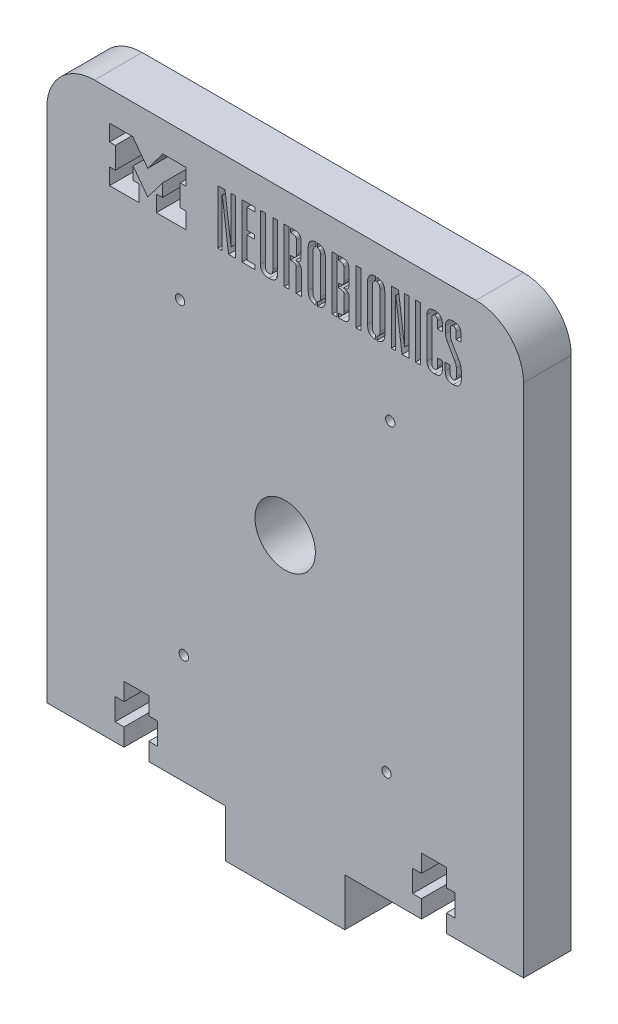
SolidWorks part; units mm, degrees
material "6061-T6 (SS)"
ref_plane "Front Plane" through (0, 0, 0) normal (0, 0, 1) x (1, 0, 0)
ref_plane "Top Plane" through (0, 0, 0) normal (0, 1, 0) x (1, 0, 0)
ref_plane "Right Plane" through (0, 0, 0) normal (1, 0, 0) x (0, 0, -1)
sketch "Sketch1" plane through (0, 0, 0) normal (0, 0, 1) x (1, 0, 0)
  line L1 (0, 0) -> (127, 0)
  line L2 (0, 0) -> (0, 150)
  line L3 (0, 150) -> (127, 150)
  line L4 (127, 0) -> (127, 150)
  dimension "D1" = 150
  dimension "D2" = 127
extrude "Boss-Extrude1" add sketch "Sketch1" along normal blind 12.7
sketch "Sketch2" plane through (0, 0, 12.7) normal (0, 0, 1) x (1, 0, 0)
  line L0 (63.5, 0) -> (63.5, 150) construction
  line L1 (0, 0) -> (127, 0) construction
  line L2 (127, 150) -> (0, 150) construction
  line L3 (23.876, 15.24) -> (23.876, 0) construction
  line L4 (20.574, 0) -> (27.178, 0)
  line L5 (20.574, 0) -> (20.574, 15.24)
  line L6 (20.574, 15.24) -> (27.178, 15.24)
  line L7 (27.178, 0) -> (27.178, 15.24)
  line L8 (18.2118, 10.541) -> (29.5402, 10.541)
  line L9 (18.2118, 10.541) -> (18.2118, 4.699)
  line L10 (18.2118, 4.699) -> (29.5402, 4.699)
  line L11 (29.5402, 10.541) -> (29.5402, 4.699)
  line L12 (18.2118, 7.62) -> (29.5402, 7.62) construction
  line L13 (108.7882, 7.62) -> (97.4598, 7.62) construction
  line L14 (103.124, 15.24) -> (103.124, 0) construction
  line L15 (97.4598, 10.541) -> (97.4598, 4.699)
  line L16 (108.7882, 4.699) -> (97.4598, 4.699)
  line L17 (108.7882, 10.541) -> (108.7882, 4.699)
  line L18 (108.7882, 10.541) -> (97.4598, 10.541)
  line L19 (99.822, 0) -> (99.822, 15.24)
  line L20 (106.426, 15.24) -> (99.822, 15.24)
  line L21 (106.426, 0) -> (106.426, 15.24)
  line L22 (106.426, 0) -> (99.822, 0)
  line L23 (0, 150) -> (0, 0) construction
  line M2 (0, 0) -> (127, 0)
  dimension "D1" = 6.604
  dimension "D2" = 11.3284
  dimension "D3" = 7.62
  dimension "D4" = 15.24
  dimension "D5" = 23.876
  dimension "D6" = 5.842
extrude "Cut-Extrude1" cut sketch "Sketch2" against normal through all contours L5 L8 L7 L6 | L5 L10 L7 L8 | L11 L8 L7 L10 | L9 L10 L5 L8 | L10 L5 L7 M2 | L21 L16 L19 M2 | L16 L21 L18 L19 | L21 L16 L17 L18 | L18 L21 L20 L19 | L16 L19 L18 L15
hole_wizard "1/4 Clearance Hole1" [suppressed] positions "Sketch5" profile "Sketch4" hole size "1/4" standard "ANSI Inch"
sketch "Sketch5" plane through (0, 0, 12.7) normal (0, 0, 1) x (1, 0, 0)
  line L4 (63.5, 150) -> (63.5, 0)
  line L5 (127, 150) -> (0, 150) construction
  line L6 (92.202, 0) -> (127, 0) construction
  point P9 (103.5, 25.4)
  point P13 (103.5, 76.2)
  dimension "D1" = 40
  dimension "D2" = 40
  dimension "D3" = 50.8
  dimension "D4" = 25.4
sketch "Sketch4" plane through (103.5, 25.4, 12.7) normal (1, 0, 0) x (0, -1, 0)
  line L0 (0, 0) -> (0, 27.4298)
  line L1 (0, 27.4298) -> (3.3782, 25.4)
  line L2 (3.3782, 25.4) -> (3.3782, 0)
  line L5 (3.3782, 0) -> (0, 0)
  line L10 (0, 27.4298) -> (-3.3782, 25.4) construction
  line L11 (0, -6.35) -> (0, 107.95) construction
  dimension "Hole Dia." = 6.7564
  dimension "Hole Depth" = 25.4
  dimension "Drill Angle" = 118
hole_wizard "CSK for 1/4 Flat Head Machine Screw2" [suppressed] positions "Sketch9" profile "Sketch8" countersink size "1/4" standard "Ansi Inch"
sketch "Sketch9" plane through (0, 0, 0) normal (0, 0, -1) x (-1, 0, 0)
  line L0 (-139.7, 174.498) -> (-127, 181.102) construction
  line L1 (-127, 155.702) -> (-139.7, 149.098) construction
  line L2 (-12.7, 149.098) -> (-25.4, 155.702) construction
  line L3 (-25.4, 181.102) -> (-12.7, 174.498) construction
  line L4 (-111.252, 114.3) -> (-104.648, 127) construction
  line L5 (-41.148, 127) -> (-47.752, 114.3) construction
  point P1 (-133.35, 177.8)
  point P5 (-133.35, 152.4)
  point P9 (-19.05, 152.4)
  point P13 (-19.05, 177.8)
  point P19 (-107.95, 120.65)
  point P23 (-44.45, 120.65)
sketch "Sketch8" plane through (133.35, 177.8, 0) normal (1, 0, 0) x (0, 1, 0)
  line L0 (0, 0) -> (0, 12.7)
  line L1 (0, 12.7) -> (3.2639, 12.7)
  line L2 (3.2639, 12.7) -> (3.2639, 3.6524)
  line L3 (3.2639, 3.6524) -> (6.4389, 0)
  line L5 (6.4389, 0) -> (0, 0)
  line L6 (-3.2639, 3.6524) -> (-6.4389, 0) construction
  line L11 (0, -6.35) -> (0, 107.95) construction
  dimension "Thru Hole Dia." = 6.5278
  dimension "Thru Hole Depth" = 12.7
  dimension "Near C'Sink Dia." = 12.8778
  dimension "Near C'Sink Angle" = 82
fillet "Fillet1" radius 12.7 2 edges at (127, 150, 6.35) (0, 150, 6.35)
sketch "Sketch11" plane through (0, 0, 0) normal (0, -1, 0) x (1, 0, 0)
  line L0 (27.178, 12.7) -> (99.822, 12.7) construction
  line L1 (47.625, 12.7) -> (79.375, 12.7)
  line L2 (47.625, 12.7) -> (47.625, 0)
  line L3 (47.625, 0) -> (79.375, 0)
  line L4 (79.375, 12.7) -> (79.375, 0)
  line L5 (27.178, 0) -> (99.822, 0) construction
  line L6 (63.5, 12.7) -> (63.5, 0) construction
  line L7 (27.178, 0) -> (27.178, 12.7) construction
  line L8 (99.822, 0) -> (99.822, 12.7) construction
  dimension "D1" = 31.75
extrude "Boss-Extrude2" add sketch "Sketch11" along normal blind 12.7
ref_plane "Plane1" through (63.5, 0, 0) normal (1, 0, 0) x (0, 0, -1)
mirror "Mirror2" [suppressed] about plane through (63.5, 0, 0) normal (1, 0, 0)
sketch "Sketch19" plane through (0, 0, 12.7) normal (0, 0, 1) x (1, 0, 0)
  line L4 (64.9193, 135.679) -> (64.9193, 134.5642)
  line L5 (64.5693, 140.9303) -> (64.5693, 142.0451)
  line L31 (46.7618, 140.4462) -> (46.7178, 140.4462)
  line L32 (58.2179, 142.0451) -> (58.2179, 130.0022)
  line L33 (74.2302, 139.7275) -> (74.2302, 129.9582)
  line L34 (77.3163, 134.5642) -> (77.3163, 128.7554)
  line L35 (94.6251, 127.6406) -> (92.9675, 140.4462)
  line L36 (104.0569, 129.5475) -> (104.0569, 131.5571)
  line L37 (107.5334, 140.0648) -> (107.5334, 138.554)
  line L38 (56.8977, 142.0451) -> (58.2179, 142.0451)
  line L39 (66.4421, 127.6406) -> (66.4421, 133.684)
  line L40 (76.0108, 127.6406) -> (76.0108, 142.0451)
  line L41 (85.4426, 129.9582) -> (85.4426, 139.7275)
  line L42 (99.5097, 142.0451) -> (99.5097, 127.6406)
  line L43 (47.4805, 142.0451) -> (49.0941, 129.7235)
  line L44 (53.3186, 135.679) -> (55.3869, 135.679)
  line L45 (66.3002, 135.1802) -> (66.3002, 135.1362)
  line L46 (80.4993, 140.3875) -> (80.4993, 136.7351)
  line L47 (77.3163, 140.9303) -> (77.3163, 135.679)
  line L48 (104.0569, 138.2753) -> (104.0569, 140.1235)
  line L49 (49.0941, 129.7235) -> (49.1381, 129.7235)
  line L50 (51.9984, 142.0451) -> (55.4895, 142.0451)
  line L51 (67.7964, 133.8014) -> (67.7964, 127.6406)
  line L52 (66.4933, 136.7204) -> (66.4933, 139.9475)
  line L53 (79.0618, 135.1802) -> (79.0618, 135.1362)
  line L54 (91.7647, 127.6406) -> (91.7647, 142.0451)
  line L55 (105.3771, 131.5571) -> (105.3771, 129.5035)
  line L56 (101.2699, 129.5035) -> (101.2699, 140.1529)
  line L57 (49.1381, 142.0451) -> (50.2969, 142.0451)
  line L58 (64.9193, 140.9303) -> (64.9193, 142.0451)
  line L59 (72.91, 129.9876) -> (72.91, 139.6835)
  line L60 (92.9235, 140.4462) -> (92.9235, 127.6406)
  line L61 (93.6863, 142.0451) -> (95.2998, 129.7235)
  line L62 (104.0569, 131.5571) -> (105.3771, 131.5571)
  line L63 (53.3186, 140.9303) -> (53.3186, 135.679)
  line L64 (55.4895, 128.7554) -> (55.4895, 127.6406)
  line L65 (64.9193, 135.679) -> (65.5105, 135.679)
  line L66 (78.0147, 140.9303) -> (77.6663, 140.9303)
  line L67 (88.7227, 129.9876) -> (88.7227, 139.6835)
  line L68 (105.3771, 140.1529) -> (105.3771, 138.2753)
  line L69 (107.8267, 137.2632) -> (109.9243, 133.6694)
  line L70 (60.2128, 130.0022) -> (60.2128, 142.0451)
  line L71 (63.2492, 142.0451) -> (64.5693, 142.0451)
  line L72 (78.1614, 134.5642) -> (77.6663, 134.5642)
  line L73 (86.7628, 139.6835) -> (86.7628, 129.9876)
  line L74 (110.3497, 138.3193) -> (109.0296, 138.3193)
  line L75 (50.2969, 127.6406) -> (48.4193, 127.6406)
  line L76 (55.4895, 140.9303) -> (53.3186, 140.9303)
  line L77 (65.3785, 140.9303) -> (64.9193, 140.9303)
  line L78 (79.1295, 136.7204) -> (79.1295, 139.9475)
  line L79 (83.6971, 142.0451) -> (83.6971, 127.6406)
  line L80 (98.1895, 127.6406) -> (98.1895, 142.0451)
  line L81 (109.0296, 140.0648) -> (109.0589, 140.0648)
  line L82 (55.4895, 142.0451) -> (55.4895, 140.9303)
  line L83 (55.4895, 127.6406) -> (51.9984, 127.6406)
  line L84 (60.2128, 142.0451) -> (61.5183, 142.0451)
  line L85 (78.4604, 127.6406) -> (77.6663, 127.6406)
  line L86 (82.3769, 142.0451) -> (83.6971, 142.0451)
  line L87 (109.0882, 129.7235) -> (109.0882, 131.7331)
  line L88 (108.7068, 133.112) -> (106.7706, 136.4857)
  line L89 (50.2969, 142.0451) -> (50.2969, 127.6406)
  line L90 (45.559, 142.0451) -> (47.4805, 142.0451)
  line L91 (64.5693, 127.6406) -> (63.2492, 127.6406)
  line L92 (70.9501, 139.6835) -> (70.9501, 129.9876)
  line L93 (92.9235, 127.6406) -> (91.7647, 127.6406)
  line L94 (95.2998, 129.7235) -> (95.3438, 129.7235)
  line L95 (106.1399, 129.6355) -> (106.1399, 131.6158)
  line L96 (48.4193, 127.6406) -> (46.7618, 140.4462)
  line L97 (45.559, 127.6406) -> (45.559, 142.0451)
  line L98 (64.9193, 142.0451) -> (65.6988, 142.0451)
  line L99 (69.63, 129.9582) -> (69.63, 139.7275)
  line L100 (96.5027, 142.0451) -> (96.5027, 127.6406)
  line L101 (91.7647, 142.0451) -> (93.6863, 142.0451)
  line L102 (99.5097, 127.6406) -> (98.1895, 127.6406)
  line L103 (106.1399, 131.6158) -> (107.46, 131.6158)
  line L104 (56.8977, 129.5769) -> (56.8977, 142.0451)
  line L105 (65.4153, 134.5642) -> (64.9193, 134.5642)
  line L106 (79.2028, 129.7382) -> (79.2028, 133.684)
  line L107 (90.0429, 139.7275) -> (90.0429, 129.9582)
  line L108 (102.5901, 140.1235) -> (102.5901, 129.5475)
  line L109 (55.3869, 134.5642) -> (53.3186, 134.5642)
  line L110 (64.5693, 140.9303) -> (64.5693, 127.6406)
  line L111 (80.558, 133.8014) -> (80.558, 129.2981)
  line L112 (77.6663, 135.679) -> (78.1467, 135.679)
  line L113 (105.3771, 138.2753) -> (104.0569, 138.2753)
  line L114 (109.0296, 138.3193) -> (109.0296, 140.0648)
  line L115 (55.3869, 135.679) -> (55.3869, 134.5642)
  line L116 (53.3186, 134.5642) -> (53.3186, 128.7554)
  line L117 (61.5183, 142.0451) -> (61.5183, 129.5769)
  line L118 (67.7964, 127.6406) -> (66.4421, 127.6406)
  line L119 (77.6663, 128.7554) -> (78.088, 128.7554)
  line L120 (83.6971, 127.6406) -> (82.3769, 127.6406)
  line L121 (110.3497, 140.1529) -> (110.3497, 138.3193)
  line L122 (46.7178, 140.4462) -> (46.7178, 127.6406)
  line L123 (49.1381, 129.7235) -> (49.1381, 142.0451)
  line L124 (67.7377, 140.3875) -> (67.7377, 136.7351)
  line L125 (76.0108, 142.0451) -> (77.3163, 142.0451)
  line L126 (82.3769, 127.6406) -> (82.3769, 142.0451)
  line L127 (95.3438, 129.7235) -> (95.3438, 142.0451)
  line L128 (106.2132, 138.3193) -> (106.2132, 140.0502)
  line L129 (46.7178, 127.6406) -> (45.559, 127.6406)
  line L130 (51.9984, 127.6406) -> (51.9984, 142.0451)
  line L131 (63.2492, 127.6406) -> (63.2492, 142.0451)
  line L132 (96.5027, 127.6406) -> (94.6251, 127.6406)
  line L133 (98.1895, 142.0451) -> (99.5097, 142.0451)
  line L134 (107.46, 131.6158) -> (107.46, 129.7235)
  line L135 (53.3186, 128.7554) -> (55.4895, 128.7554)
  line L136 (66.4421, 133.684) -> (66.4567, 133.684)
  line L137 (95.3438, 142.0451) -> (96.5027, 142.0451)
  line L138 (92.9675, 140.4462) -> (92.9235, 140.4462)
  line L139 (110.4084, 131.9092) -> (110.4084, 129.6355)
  line L142 (77.6663, 135.679) -> (77.6663, 134.5642)
  line L143 (77.3163, 140.9303) -> (77.3163, 142.0451)
  line L144 (77.3163, 135.679) -> (77.3163, 134.5642)
  line L145 (77.6663, 142.0451) -> (77.6663, 140.9303)
  line L146 (77.3163, 128.7554) -> (77.3163, 127.6406)
  line L147 (77.6663, 128.7554) -> (77.6663, 127.6406)
  line L148 (77.6663, 142.0451) -> (78.4604, 142.0451)
  line L149 (77.3163, 127.6406) -> (76.0108, 127.6406)
  line L150 (87.5677, 142.1583) -> (87.5677, 141.0219)
  line L151 (87.9177, 142.1583) -> (87.9177, 141.0219)
  line L152 (87.7427, 142.1624) -> (87.7427, 127.5233) construction
  line L153 (87.5677, 128.6492) -> (87.5677, 127.5274)
  line L154 (87.9177, 128.6492) -> (87.9177, 127.5274)
  line L155 (71.9301, 142.1624) -> (71.9301, 127.5233) construction
  line L156 (71.7551, 142.1583) -> (71.7551, 141.0219)
  line L157 (72.1051, 142.1583) -> (72.1051, 141.0219)
  line L158 (72.1051, 128.6492) -> (72.1051, 127.5274)
  line L159 (71.7551, 128.6492) -> (71.7551, 127.5274)
  spline S0 degree 3 poles (80.558, 129.2981) (80.558, 127.8606) (79.7806, 127.6406) (78.4604, 127.6406) knots 0 0 0 0 1 1 1 1
  spline S1 degree 3 poles (78.1467, 135.679) (78.7628, 135.679) (79.1295, 135.855) (79.1295, 136.7204) knots 0 0 0 0 1 1 1 1
  spline S2 degree 3 poles (108.2961, 127.5233) (106.844, 127.5233) (106.1399, 128.1834) (106.1399, 129.6355) knots 0 0 0 0 1 1 1 1
  spline S3 degree 3 poles (67.7377, 136.7351) (67.7377, 135.6203) (67.3123, 135.2389) (66.3002, 135.1802) knots 0 0 0 0 1 1 1 1
  spline S4 degree 3 poles (79.2028, 133.684) (79.2028, 134.3881) (78.7774, 134.5642) (78.1614, 134.5642) knots 0 0 0 0 1 1 1 1
  spline S5 degree 3 poles (109.0589, 140.0648) (109.0589, 140.6222) (108.9122, 141.0476) (108.2961, 141.0476) knots 0 0 0 0 1 1 1 1
  spline S6 degree 3 poles (108.2815, 142.1624) (109.763, 142.1624) (110.3497, 141.4583) (110.3497, 140.1529) knots 0 0 0 0 1 1 1 1
  spline S7 degree 3 poles (58.2179, 130.0022) (58.2179, 128.9608) (58.5552, 128.6527) (59.2153, 128.6527) knots 0 0 0 0 1 1 1 1
  spline S8 degree 3 poles (66.3002, 135.1362) (67.239, 135.0775) (67.7964, 134.7988) (67.7964, 133.8014) knots 0 0 0 0 1 1 1 1
  spline S9 degree 3 poles (65.5105, 135.679) (66.1266, 135.679) (66.4933, 135.855) (66.4933, 136.7204) knots 0 0 0 0 1 1 1 1
  spline S10 degree 3 poles (102.5901, 129.5475) (102.5901, 128.9314) (102.8101, 128.6234) (103.3235, 128.6234) knots 0 0 0 0 1 1 1 1
  spline S11 degree 3 poles (103.3235, 142.1478) (104.7023, 142.1478) (105.3771, 141.3703) (105.3771, 140.1529) knots 0 0 0 0 1 1 1 1
  spline S12 degree 3 poles (66.4933, 139.9475) (66.4933, 140.7836) (66.0532, 140.9303) (65.3785, 140.9303) knots 0 0 0 0 1 1 1 1
  spline S13 degree 3 poles (87.9177, 128.6492) (88.5867, 128.7311) (88.7227, 129.2605) (88.7227, 129.9876) knots 0.082067 0.082067 0.082067 0.082067 1 1 1 1
  spline S14 degree 3 poles (74.2302, 129.9582) (74.2302, 128.5882) (73.727, 127.5989) (72.1051, 127.5274) knots 0 0 0 0 0.962899 0.962899 0.962899 0.962899
  spline S15 degree 3 poles (87.5677, 141.0219) (86.8987, 140.9399) (86.7628, 140.4106) (86.7628, 139.6835) knots 0.082067 0.082067 0.082067 0.082067 1 1 1 1
  spline S16 degree 3 poles (103.3235, 141.0476) (102.8101, 141.0476) (102.5901, 140.7543) (102.5901, 140.1235) knots 0 0 0 0 1 1 1 1
  spline S17 degree 3 poles (107.5334, 138.554) (107.5334, 138.0993) (107.6067, 137.6299) (107.8267, 137.2632) knots 0 0 0 0 1 1 1 1
  spline S18 degree 3 poles (87.9177, 142.1583) (89.5396, 142.0868) (90.0429, 141.0975) (90.0429, 139.7275) knots 0.037101 0.037101 0.037101 0.037101 1 1 1 1
  spline S19 degree 3 poles (87.5677, 127.5274) (85.9458, 127.5989) (85.4426, 128.5882) (85.4426, 129.9582) knots 0.037102 0.037102 0.037102 0.037102 1 1 1 1
  spline S20 degree 3 poles (101.2699, 140.1529) (101.2699, 141.3703) (101.9447, 142.1478) (103.3235, 142.1478) knots 0 0 0 0 1 1 1 1
  spline S21 degree 3 poles (59.186, 127.5233) (58.0859, 127.5233) (56.8977, 127.978) (56.8977, 129.5769) knots 0 0 0 0 1 1 1 1
  spline S22 degree 3 poles (71.7551, 127.5274) (70.1332, 127.5989) (69.63, 128.5882) (69.63, 129.9582) knots 0.037101 0.037101 0.037101 0.037101 1 1 1 1
  spline S23 degree 3 poles (71.7551, 141.0219) (71.0861, 140.9399) (70.9501, 140.4106) (70.9501, 139.6835) knots 0.082067 0.082067 0.082067 0.082067 1 1 1 1
  spline S24 degree 3 poles (108.2961, 141.0476) (107.6801, 141.0476) (107.5334, 140.6222) (107.5334, 140.0648) knots 0 0 0 0 1 1 1 1
  spline S25 degree 3 poles (110.4084, 129.6355) (110.4084, 128.286) (109.6163, 127.5233) (108.2961, 127.5233) knots 0 0 0 0 1 1 1 1
  spline S26 degree 3 poles (72.1051, 142.1583) (73.727, 142.0868) (74.2302, 141.0975) (74.2302, 139.7275) knots 0.037101 0.037101 0.037101 0.037101 1 1 1 1
  spline S27 degree 3 poles (70.9501, 129.9876) (70.9501, 129.2605) (71.0861, 128.7311) (71.7551, 128.6492) knots 0 0 0 0 0.917933 0.917933 0.917933 0.917933
  spline S28 degree 3 poles (78.088, 128.7554) (78.7628, 128.7554) (79.2028, 128.9021) (79.2028, 129.7382) knots 0 0 0 0 1 1 1 1
  spline S29 degree 3 poles (109.9243, 133.6694) (110.2177, 133.1706) (110.4084, 132.5546) (110.4084, 131.9092) knots 0 0 0 0 1 1 1 1
  spline S30 degree 3 poles (80.4993, 136.7351) (80.4993, 135.6203) (80.0739, 135.2242) (79.0618, 135.1802) knots 0 0 0 0 1 1 1 1
  spline S31 degree 3 poles (86.7628, 129.9876) (86.7628, 129.2605) (86.8987, 128.7311) (87.5677, 128.6492) knots 0 0 0 0 0.917933 0.917933 0.917933 0.917933
  spline S32 degree 3 poles (106.2132, 140.0502) (106.2132, 141.473) (106.9466, 142.1624) (108.2815, 142.1624) knots 0 0 0 0 1 1 1 1
  spline S33 degree 3 poles (59.2153, 128.6527) (59.8901, 128.6527) (60.2128, 128.9755) (60.2128, 130.0022) knots 0 0 0 0 1 1 1 1
  spline S34 degree 3 poles (90.0429, 129.9582) (90.0429, 128.5882) (89.5396, 127.5989) (87.9177, 127.5274) knots 0 0 0 0 0.962899 0.962899 0.962899 0.962899
  spline S35 degree 3 poles (108.2961, 128.6527) (108.8389, 128.6527) (109.0882, 129.0488) (109.0882, 129.7235) knots 0 0 0 0 1 1 1 1
  spline S36 degree 3 poles (106.7706, 136.4857) (106.4186, 137.1018) (106.2132, 137.5859) (106.2132, 138.3193) knots 0 0 0 0 1 1 1 1
  spline S37 degree 3 poles (72.1051, 128.6492) (72.7741, 128.7311) (72.91, 129.2605) (72.91, 129.9876) knots 0.082067 0.082067 0.082067 0.082067 1 1 1 1
  spline S38 degree 3 poles (85.4426, 139.7275) (85.4426, 141.0975) (85.9458, 142.0868) (87.5677, 142.1583) knots 0 0 0 0 0.962898 0.962898 0.962898 0.962898
  spline S39 degree 3 poles (61.5183, 129.5769) (61.5183, 127.978) (60.3155, 127.5233) (59.186, 127.5233) knots 0 0 0 0 1 1 1 1
  spline S40 degree 3 poles (79.1295, 139.9475) (79.1295, 140.7836) (78.6894, 140.9303) (78.0147, 140.9303) knots 0 0 0 0 1 1 1 1
  spline S41 degree 3 poles (103.3235, 128.6234) (103.8369, 128.6234) (104.0569, 128.9168) (104.0569, 129.5475) knots 0 0 0 0 1 1 1 1
  spline S42 degree 3 poles (105.3771, 129.5035) (105.3771, 128.286) (104.7023, 127.5086) (103.3235, 127.5086) knots 0 0 0 0 1 1 1 1
  spline S43 degree 3 poles (72.91, 139.6835) (72.91, 140.4106) (72.7741, 140.9399) (72.1051, 141.0219) knots 0 0 0 0 0.917933 0.917933 0.917933 0.917933
  spline S44 degree 3 poles (88.7227, 139.6835) (88.7227, 140.4106) (88.5867, 140.9399) (87.9177, 141.0219) knots 0 0 0 0 0.917933 0.917933 0.917933 0.917933
  spline S45 degree 3 poles (107.46, 129.7235) (107.46, 129.0488) (107.7241, 128.6527) (108.2961, 128.6527) knots 0 0 0 0 1 1 1 1
  spline S46 degree 3 poles (109.0882, 131.7331) (109.0882, 132.2319) (108.9855, 132.6132) (108.7068, 133.112) knots 0 0 0 0 1 1 1 1
  spline S47 degree 3 poles (65.6988, 142.0451) (66.9603, 142.0451) (67.7377, 141.8251) (67.7377, 140.3875) knots 0 0 0 0 1 1 1 1
  spline S48 degree 3 poles (69.63, 139.7275) (69.63, 141.0975) (70.1332, 142.0868) (71.7551, 142.1583) knots 0 0 0 0 0.962899 0.962899 0.962899 0.962899
  spline S49 degree 3 poles (78.4604, 142.0451) (79.7219, 142.0451) (80.4993, 141.8251) (80.4993, 140.3875) knots 0 0 0 0 1 1 1 1
  spline S50 degree 3 poles (66.4567, 133.684) (66.4567, 134.3881) (66.0313, 134.5642) (65.4153, 134.5642) knots 0 0 0 0 1 1 1 1
  spline S51 degree 3 poles (79.0618, 135.1362) (79.9859, 135.0922) (80.558, 134.7988) (80.558, 133.8014) knots 0 0 0 0 1 1 1 1
  spline S52 degree 3 poles (104.0569, 140.1235) (104.0569, 140.7396) (103.8369, 141.0476) (103.3235, 141.0476) knots 0 0 0 0 1 1 1 1
  spline S53 degree 3 poles (103.3235, 127.5086) (101.9447, 127.5086) (101.2699, 128.286) (101.2699, 129.5035) knots 0 0 0 0 1 1 1 1
  dimension "D1" = 0.35
  dimension "D2" = 0.35
  dimension "D3" = 0.175
  dimension "D4" = 0.175
  dimension "D5" = 0.175
  dimension "D6" = 0.175
sketch "Sketch20" plane through (0, 0, 12.7) normal (0, 0, 1) x (1, 0, 0)
  line L0 (7.2814, 142.1428) -> (71.0354, 142.1428) construction
  line L1 (7.2814, 127.6014) -> (73.4515, 127.6014) construction
  line L7 (22.9767, 131.9734) -> (24.6043, 131.9734)
  line L8 (24.6043, 131.9734) -> (24.6043, 127.6406)
  line L9 (24.6043, 127.6406) -> (16.7149, 127.6406)
  line L10 (16.7149, 127.6406) -> (16.7149, 131.9734)
  line L11 (16.7149, 131.9734) -> (18.2543, 131.9734)
  line L12 (18.2543, 131.9734) -> (18.2543, 137.7006)
  line L13 (18.2543, 137.7006) -> (16.7141, 137.7006)
  line L14 (16.7141, 137.7006) -> (16.7141, 142.0451)
  line L15 (16.7141, 142.0451) -> (22.8903, 142.0451)
  line L16 (22.8903, 142.0451) -> (26.9017, 136.7302)
  line L17 (26.9017, 136.7302) -> (30.913, 142.0451)
  line L18 (30.913, 142.0451) -> (37.0893, 142.0451)
  line L19 (37.0893, 142.0451) -> (37.0893, 137.7006)
  line L20 (37.0893, 137.7006) -> (35.549, 137.7006)
  line L21 (35.549, 137.7006) -> (35.549, 131.9734)
  line L22 (35.549, 131.9734) -> (37.0885, 131.9734)
  line L23 (37.0885, 131.9734) -> (37.0885, 127.6406)
  line L24 (37.0885, 127.6406) -> (29.1991, 127.6406)
  line L25 (29.1991, 127.6406) -> (29.1991, 131.9734)
  line L26 (29.1991, 131.9734) -> (30.8267, 131.9734)
  line L27 (30.8267, 131.9734) -> (30.8267, 135.3211)
  line L28 (30.8267, 135.3211) -> (26.9017, 130.1206)
  line L29 (26.9017, 130.1206) -> (22.9767, 135.3211)
  line L30 (22.9767, 135.3211) -> (22.9767, 131.9734)
extrude "Cut-Extrude9" cut sketch "Sketch20" against normal through all
extrude "Cut-Extrude10" cut sketch "Sketch19" against normal through all
sketch "Sketch21" plane through (0, 0, 12.7) normal (0, 0, 1) x (1, 0, 0)
  line L0 (0, 70.3826) -> (127, 70.3826) construction
  line L1 (0, 137.3) -> (0, 0) construction
  line L2 (127, 0) -> (127, 137.3) construction
  line L3 (79.375, -12.7) -> (47.625, -12.7) construction
  circle A0 centre (63.5, 70.3826) radius 8.05
  dimension "D2" = 16.1
  dimension "D1" = 83.0826
extrude "Cut-Extrude11" cut sketch "Sketch21" against normal through all contours A0
hole_wizard "M3x0.5 Tapped Hole1" positions "Sketch23" profile "Sketch24" tap size "M3x0.5" standard "ANSI Metric" end condition through all
sketch "Sketch23" plane through (0, 0, 12.7) normal (0, 0, 1) x (1, 0, 0)
  line L0 (27.178, 0) -> (47.625, 0) construction
  line L1 (63.5, -12.7) -> (63.5, 150) construction
  line L2 (79.375, -12.7) -> (47.625, -12.7) construction
  line L3 (114.3, 150) -> (12.7, 150) construction
  point P2 (35.5, 110.7207)
  point P4 (36.5, 29.21)
  dimension "D1" = 29.21
  dimension "D2" = 27
  dimension "D3" = 28
  dimension "D4" = 39.2793
sketch "Sketch24" plane through (35.5, 110.7207, 12.7) normal (1, 0, 0) x (0, -1, 0)
  line L0 (0, 0) -> (0, 12.7)
  line L1 (0, 12.7) -> (1.25, 12.7)
  line L2 (1.25, 12.7) -> (1.25, 0)
  line L5 (1.25, 0) -> (0, 0)
  line L11 (0, -6.35) -> (0, 107.95) construction
  dimension "Thru Tap Drill Dia." = 2.5
  dimension "Thru Tap Drill Depth" = 12.7
cosmetic thread "Hole Thread2" parameters "D2"=3
cosmetic thread "Hole Thread3" parameters "D2"=3
mirror "Mirror3" about plane through (63.5, 0, 0) normal (1, 0, 0) of "M3x0.5 Tapped Hole1"
fillet "Fillet2" radius 0.25 2 edges at (24.6043, 131.9734, 6.35) (29.1991, 131.9734, 6.35)
sketch "Sketch25" plane through (0, -12.7, 0) normal (0, -1, 0) x (1, 0, 0)
  point P4 (63.5, 6.35)
